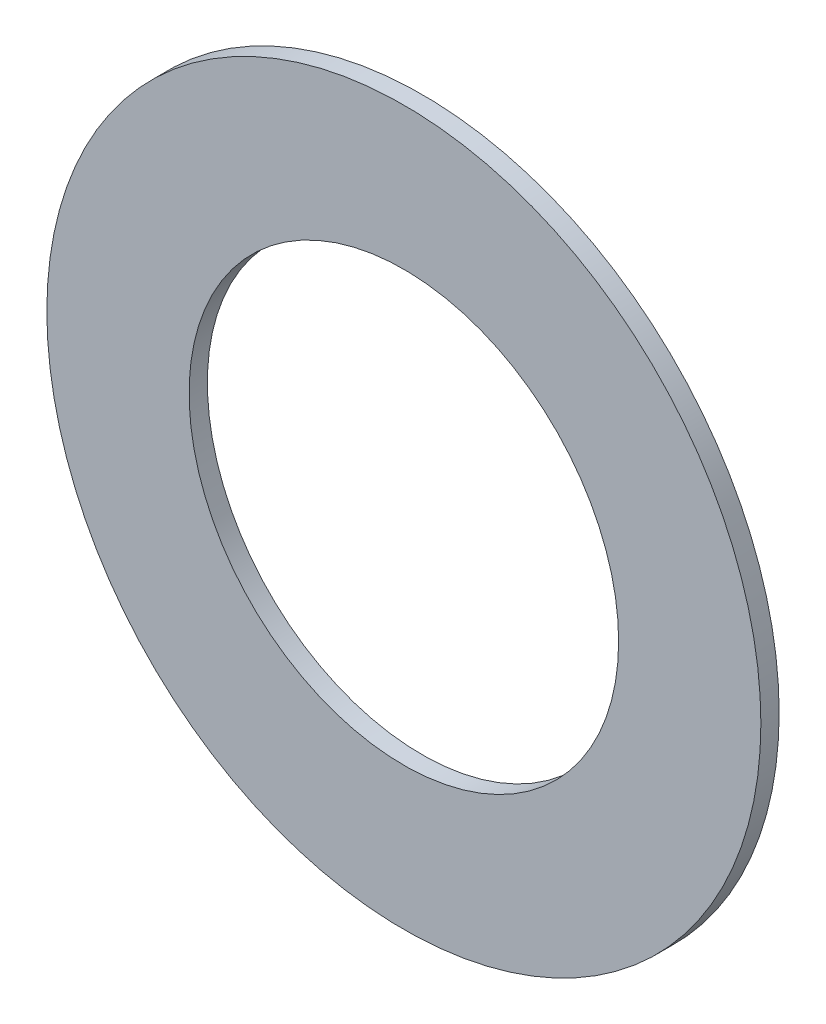
SolidWorks part; units mm, degrees
material "Alloy Steel"
ref_plane "Front Plane" through (0, 0, 0) normal (0, 0, 1) x (1, 0, 0)
ref_plane "Top Plane" through (0, 0, 0) normal (0, 1, 0) x (1, 0, 0)
ref_plane "Right Plane" through (0, 0, 0) normal (1, 0, 0) x (0, 0, -1)
sketch "Sketch1" plane through (0, 0, 0) normal (0, 0, 1) x (1, 0, 0)
  line L0 (-9.525, 0) -> (9.525, 0) construction
  circle A0 centre (0, 0) radius 15.875 construction
  circle A1 centre (0, 0) radius 9.5504 construction
  dimension "OD" = 31.75
  dimension "ID" = 19.1008
  dimension "For Shaft Diameter" = 19.05
sketch "Sketch2" plane through (0, 0, 0) normal (1, 0, 0) x (0, 0, -1)
  line L4 (0.4064, 15.875) -> (-0.4064, 15.875) construction
  point P0 (0, 15.875)
  dimension "Thickness" = 0.8128
sketch "Sketch3" plane through (0, 0, 0) normal (0, 0, 1) x (1, 0, 0)
  circle A0 centre (0, 0) radius 9.5504 construction
  circle A1 centre (0, 0) radius 15.875 construction
  circle A3 centre (0, 0) radius 9.5504
  circle A5 centre (0, 0) radius 15.875
extrude "Boss-Extrude1" add sketch "Sketch3" against normal up to vertex (0.4064 mm away) and the other way up to vertex (0.4064 mm away)
equation "\"D1\"= \"Thickness@Sketch2\""
